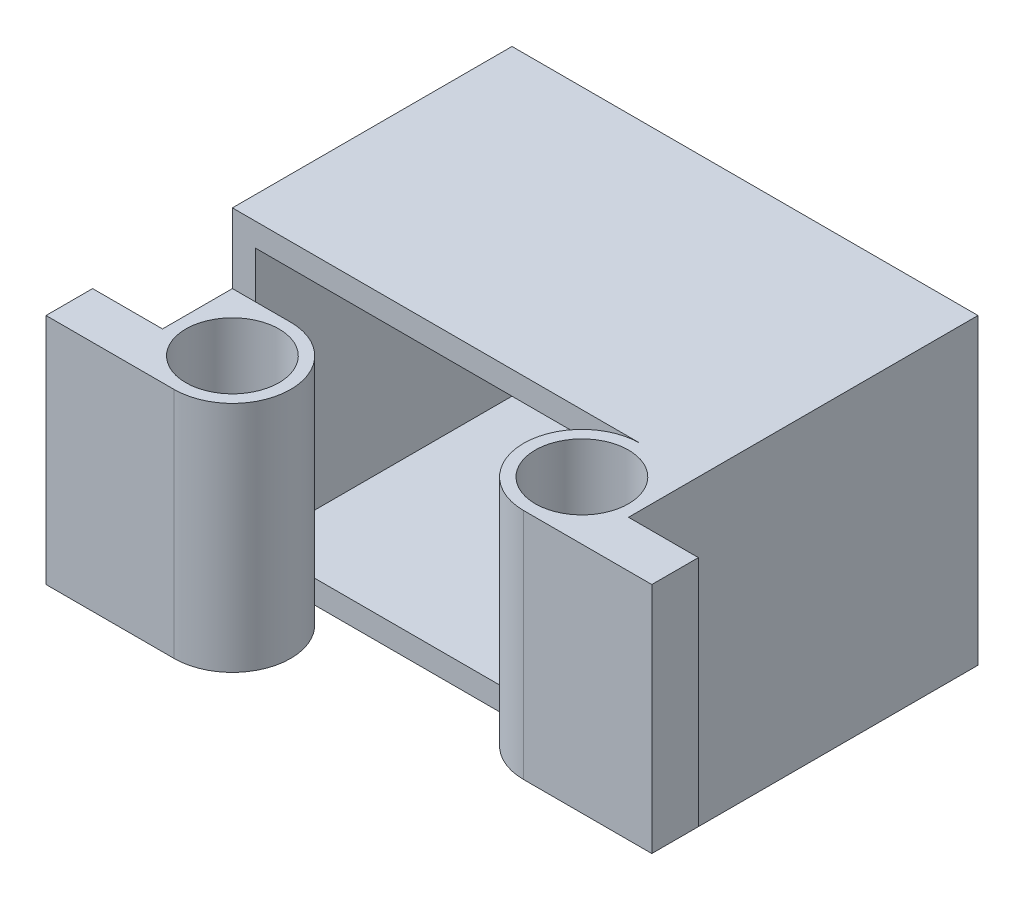
SolidWorks part; units mm, degrees
ref_plane "정면" through (0, 0, 0) normal (0, 0, 1) x (1, 0, 0)
ref_plane "윗면" through (0, 0, 0) normal (0, 1, 0) x (1, 0, 0)
ref_plane "우측면" through (0, 0, 0) normal (1, 0, 0) x (0, 0, -1)
sketch "스케치1" plane through (0, 0, 0) normal (0, 0, 1) x (1, 0, 0)
  line L1 (-10, -6.5) -> (10, -6.5)
  line L2 (-10, -6.5) -> (-10, 6.5)
  line L3 (-10, 6.5) -> (10, 6.5)
  line L4 (10, -6.5) -> (10, 6.5)
  line L5 (-10, -6.5) -> (10, 6.5) construction
  line L6 (-10, 6.5) -> (10, -6.5) construction
  point P0 (0, 0)
  dimension "D1" = 13
  dimension "D2" = 20
extrude "보스-돌출1" add sketch "스케치1" along normal blind 12
shell "쉘1" thickness 1
ref_plane "평면1" through (0, 3.5, 0) normal (0, 1, 0) x (1, 0, 0)
sketch "스케치2" plane through (0, 3.5, 0) normal (0, 1, 0) x (1, 0, 0)
  line L0 (10, -12) -> (-10, -12) construction
  line L2 (-10, -12) -> (-10, 0) construction
  line L3 (-10, -12) -> (-10, -14.5)
  line L5 (-10, -14.5) -> (-10, -17)
  line L6 (-10, -17) -> (-7.5, -17)
  line L9 (-10, -12) -> (-7.5, -12)
  circle A0 centre (-7.5, -14.5) radius 2.5
  circle A2 centre (-7.5, -14.5) radius 2
  dimension "D2" = 5
  dimension "D3" = 4
extrude "보스-돌출4" add sketch "스케치2" against normal blind 10 separate body contours A0 L5 L6 | A0 A2 | A0 L9 L3
sketch "스케치3" plane through (0, 0, 1) normal (0, 0, 1) x (1, 0, 0)
  circle A0 centre (0, 0) radius 4.9
  dimension "D1" = 9.8
extrude "컷-돌출1" cut sketch "스케치3" against normal blind 0.2
sketch "스케치9" plane through (0, 6.5, 0) normal (0, 1, 0) x (1, 0, 0)
  line L0 (10, -12) -> (10, -14.5)
  line L1 (7.5, -17) -> (10, -17)
  line L2 (10, -17) -> (10, -14.5)
  line L3 (10, -12) -> (7.5, -12)
  circle A0 centre (7.5, -14.5) radius 2.5
  circle A1 centre (7.5, -14.5) radius 2
  line M3 (-10, -12) -> (10, -12)
  dimension "D1" = 5
  dimension "D2" = 4
extrude "보스-돌출8" add sketch "스케치9" against normal blind 10 contours A0 L0 M3 | A0 L1 L2 | A0 A1
sketch "스케치6" plane through (-10, 0, 0) normal (-1, 0, 0) x (0, 0, 1)
  line L0 (12, -6.5) -> (17, -6.5) construction
  line L1 (17, 3.5) -> (15, 3.5)
  line L2 (17, 3.5) -> (17, -6.5)
  line L3 (17, -6.5) -> (15, -6.5)
  line L4 (15, 3.5) -> (15, -6.5)
  line L6 (12, -6.5) -> (17, -6.5) construction
  line L7 (17, -6.5) -> (17, 3.5) construction
  line L8 (12, 3.5) -> (17, 3.5) construction
  dimension "D1" = 2
extrude "보스-돌출10" add sketch "스케치6" along normal blind 3
sketch "스케치10" plane through (10, 0, 0) normal (1, 0, 0) x (0, 0, -1)
  line L0 (-12, -3.5) -> (-17, -3.5) construction
  line L1 (-17, 6.5) -> (-15, 6.5)
  line L2 (-17, 6.5) -> (-17, -3.5)
  line L3 (-17, -3.5) -> (-15, -3.5)
  line L4 (-15, 6.5) -> (-15, -3.5)
  dimension "D1" = 2
extrude "보스-돌출11" add sketch "스케치10" along normal blind 3
scale "축척1" scale about origin uniform scaling yes scale factor 2
